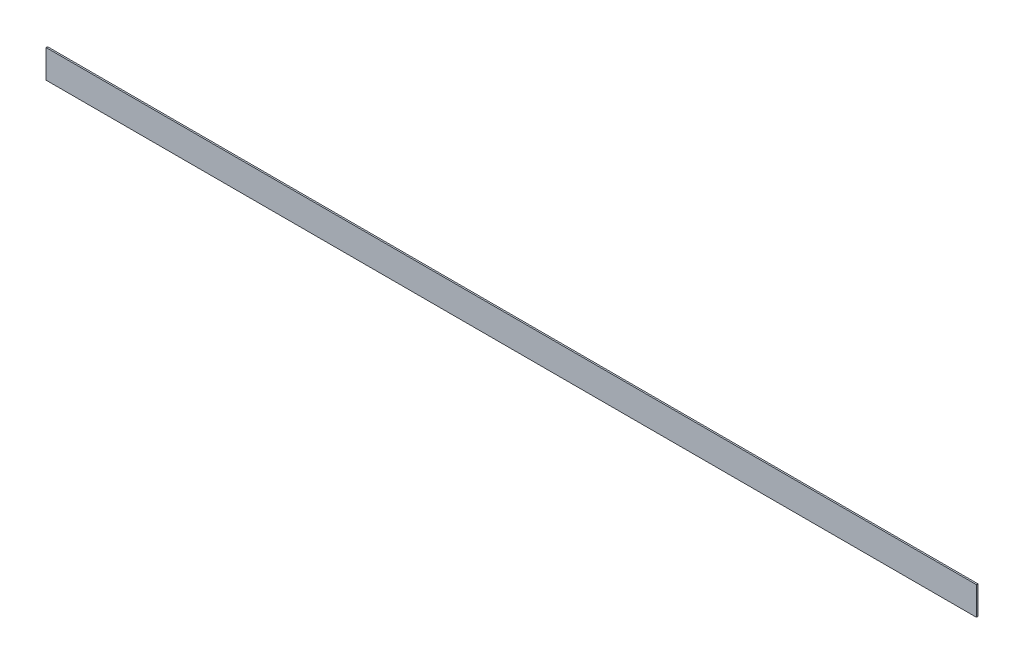
SolidWorks part; units mm, degrees
ref_plane "Front" through (0, 0, 0) normal (0, 0, 1) x (1, 0, 0)
ref_plane "Top" through (0, 0, 0) normal (0, 1, 0) x (1, 0, 0)
ref_plane "Right" through (0, 0, 0) normal (1, 0, 0) x (0, 0, -1)
sketch "Sketch1" plane through (0, 0, 0) normal (0, 0, 1) x (1, 0, 0)
  line L1 (-1318.731, 0) -> (14522.2008, 0)
  line L2 (-1318.731, 0) -> (-1318.731, 481.4963)
  line L3 (-1318.731, 481.4963) -> (14522.2008, 481.4963)
  line L4 (14522.2008, 0) -> (14522.2008, 481.4963)
  point P4 (-1798.9975, 0)
  point P5 (-1318.731, 0)
  point P6 (0, 0)
extrude "Boss-Extrude1" add sketch "Sketch1" along normal blind 25.4
